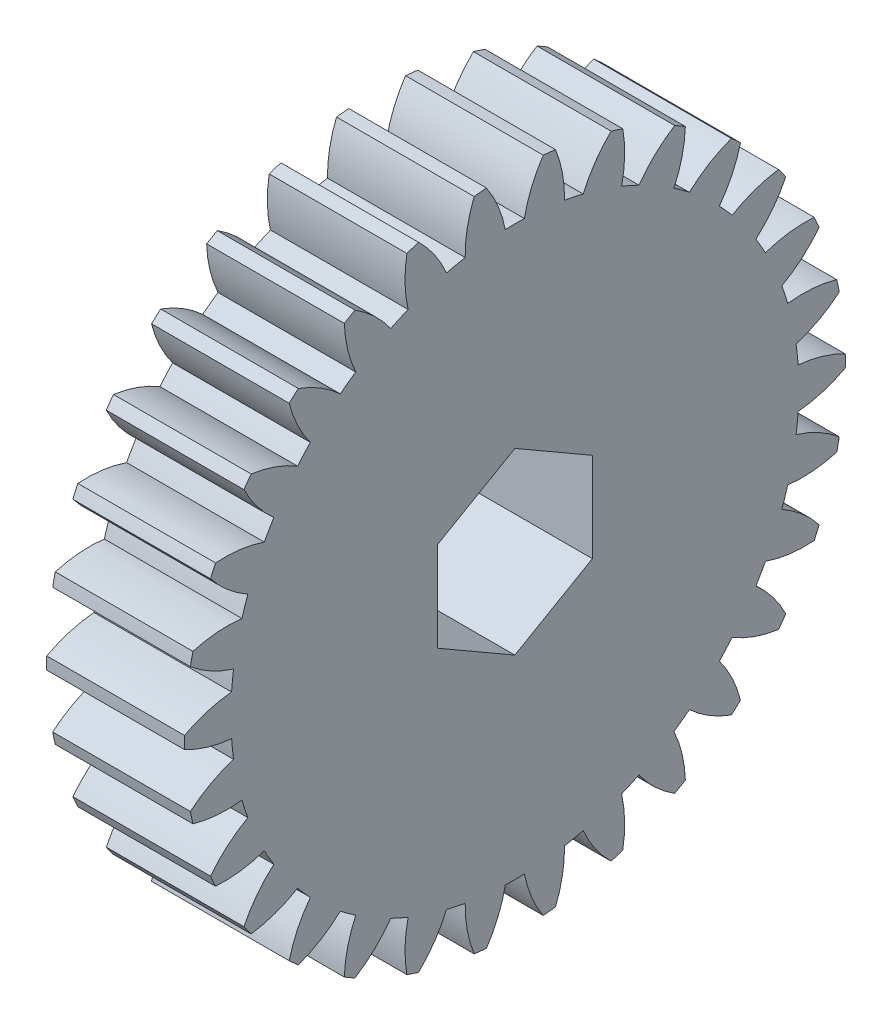
SolidWorks part; units mm, degrees
material "AISI 4340 Aço, normalizado"
ref_plane "Plane1" through (0, 0, 0) normal (0, 0, 1) x (1, 0, 0)
ref_plane "Plane2" through (0, 0, 0) normal (0, 1, 0) x (1, 0, 0)
ref_plane "Plane3" through (0, 0, 0) normal (1, 0, 0) x (0, 0, -1)
sketch "HoldingSke" plane through (0, 0, 0) normal (0, 1, 0) x (1, 0, 0)
  line L0 (0, 0) -> (0.5774, -0.3333)
  line L1 (-15, 0) -> (100, 0) construction
  line L2 (0, 0) -> (-2.1039, 2.3779)
  line L3 (0, 0) -> (-11.863, 4.5341)
  line L4 (0, 0) -> (7.479, 4.318)
  line L5 (0, 0) -> (-46.8476, -17.4728)
  line L6 (0, 0) -> (-12.4344, -8.3896)
  line L7 (-2.1039, 2.3779) -> (8.6586, 51.2059)
  line L8 (-76.2, 54.61) -> (-74.4, 54.61)
  line L9 (-71.009, 38.7566) -> (-53.1078, 45.2721)
  line L10 (-76.2, 71.12) -> (104.1128, 71.12)
  line L11 (0, 0) -> (-15, 0)
  line L12 (-76.2, 101.6) -> (-76.147, 101.6)
  line L13 (24.9733, 27.94) -> (52.9518, 28.4284)
  line L14 (24.9733, 27.94) -> (24.9743, 27.94)
  line L15 (24.9733, 27.94) -> (100.4006, 29.5858)
  line L16 (-63.627, -1.5) -> (-12.827, -1.5)
  circle A0 centre (0, 0) radius 5
  circle A1 centre (0, 0) radius 20.624
  circle A2 centre (0, 0) radius 37.5
  circle A3 centre (0, 0) radius 5
  dimension "MHD" = 41.248
  dimension "Hub_dia" = 75
  dimension "Bore" = 10
  dimension "MBD" = 10
  dimension "Num_teeth" = 30
  dimension "Pitch" = 0.6667
  dimension "Overall_len" = 50
  dimension "Show_teeth" = 30
  dimension "Thickness" = 15
  dimension "OAL" = 50.0001
  dimension "T_dim" = 1.8
  dimension "Ap" = 20
  dimension "H" = 19.05
  dimension "Pitch_radius" = 180.3128
  dimension "Width" = 15
  dimension "Backlash" = 0.053
  dimension "Addendum_fac" = 1
  dimension "Dedendum_fac" = 1.25
  dimension "Clearance_fac" = 0.25
  dimension "Dedendum_add" = 0.001
  dimension "Module" = 1.5
sketch "BasProSke" plane through (0, 0, 0) normal (0, 1, 0) x (1, 0, 0)
  line L0 (-10, 0) -> (60, 0) construction
  line L1 (0, 0) -> (0, 24)
  line L2 (0, 0) -> (15, 0)
  line L3 (15, 0) -> (15, 24)
  line L4 (15, 24) -> (0, 24)
  dimension "Thickness" = 15
  dimension "Diameter" = 48
revolve "Base-Revolve" add sketch "BasProSke" angle 360 about L0
sketch "TooCutSke" plane through (0, 0, 0) normal (1, 0, 0) x (0, 0, -1)
  line L1 (0, 0) -> (0, 107) construction
  line L2 (0, 0) -> (-1.2703, 22.4641) construction
  line L3 (0, 0) -> (-4.6983, 44.7014) construction
  line L4 (-1.2703, 22.4641) -> (-2.3492, 22.3507) construction
  arc A0 (0.6933, 20.6123) -> (-0.6933, 20.6123) centre (0, 0) ccw
  arc A1 (2.0805, 23.9351) -> (-2.0805, 23.9351) centre (0, 0) ccw
  circle A2 centre (0, 0) radius 22.5 construction
  circle A3 centre (0, 0) radius 21.1431 construction
  arc A4 (-0.6933, 20.6123) -> (-2.0805, 23.9351) centre (-9.5243, 18.8764) ccw
  arc A5 (2.0805, 23.9351) -> (0.6933, 20.6123) centre (9.5243, 18.8764) ccw
  dimension "Root_dia" = 41.248
  dimension "Overcut_dia" = 48.0508
  dimension "Pitch_dia" = 45
  dimension "Base_dia" = 42.2862
  dimension "Flank_rad" = 9
  dimension "Half_ang" = 6
  dimension "Half_CT" = 1.0848
extrude "ToothCut" cut sketch "TooCutSke" along normal through all
fillet "Breaks" [suppressed] radius 0.03
fillet "RootFillets" [suppressed] radius 0.376
pattern_circular "TeethCuts" count 30 every 12 about axis through (-10, 0, 0) along (1, 0, 0) of "ToothCut", "RootFillets", "Breaks"
sketch "HubNeaOneSke" plane through (0, 0, 0) normal (-1, 0, 0) x (0, 0, 1)
  circle A0 centre (0, 0) radius 20.624
  dimension "Diameter" = 41.248
extrude "HubNearOne" [suppressed] add sketch "HubNeaOneSke" along normal blind 35.0001
sketch "HubNeaBotSke" plane through (0, 0, 0) normal (-1, 0, 0) x (0, 0, 1)
  circle A0 centre (0, 0) radius 20.624
  dimension "Diameter" = 41.248
extrude "HubNearBoth" [suppressed] add sketch "HubNeaBotSke" along normal blind 17.5
ref_plane "FarPln" through (15, 0, 0) normal (1, 0, 0) x (0, 0, -1)
sketch "HubFarSke" plane through (15, 0, 0) normal (1, 0, 0) x (0, 0, -1)
  circle A0 centre (0, 0) radius 20.624
  dimension "Diameter" = 41.248
extrude "HubFar" [suppressed] add sketch "HubFarSke" along normal blind 17.5
sketch "BorSke" plane through (0, 0, 0) normal (1, 0, 0) x (0, 0, -1)
  circle A0 centre (0, 0) radius 5
  dimension "Diameter" = 10
extrude "Bore" cut sketch "BorSke" along normal mid plane 100.0001
sketch "KeySke" plane through (0, 0, 0) normal (1, 0, 0) x (0, 0, -1)
  line L0 (-2, 0) -> (-2, 6.8)
  line L1 (-2, 6.8) -> (2, 6.8)
  line L2 (2, 6.8) -> (2, 0)
  line L3 (0, 0) -> (0, 34) construction
  line L4 (-2, 0) -> (2, 0)
  dimension "Offset" = 6.8
  dimension "Width" = 4
extrude "Keyway" [suppressed] cut sketch "KeySke" along normal mid plane 100.0001
pattern_circular "Keyway2" [suppressed] count 2 every 90 about axis through (-10, 0, 0) along (1, 0, 0)
sketch "Esboço1" plane through (15, 0, 0) normal (1, 0, 0) x (0, 0, -1)
  line L0 (0, 0) -> (5, 0) construction
  line L1 (0, 6.5) -> (-5.6292, 3.25)
  line L2 (-5.6292, 3.25) -> (-5.6292, -3.25)
  line L3 (-5.6292, -3.25) -> (0, -6.5)
  line L4 (0, -6.5) -> (5.6292, -3.25)
  line L5 (5.6292, -3.25) -> (5.6292, 3.25)
  line L6 (5.6292, 3.25) -> (0, 6.5)
  line L7 (0, 0) -> (0, 6.5) construction
  circle A0 centre (0, 0) radius 5.6292 construction
  circle A1 centre (0, 0) radius 5 construction
  dimension "D1" = 90
  dimension "D2" = 13
extrude "Corte-extrusão1" cut sketch "Esboço1" against normal through all
sketch "Esboço2" plane through (0, 0, 0) normal (-1, 0, 0) x (0, 0, 1)
  circle A0 centre (0, 0) radius 30.6034
extrude "Corte-extrusão2" cut sketch "Esboço2" against normal blind 5
sketch "Esboço4" plane through (5, 0, 0) normal (-1, 0, 0) x (0, 0, 1)
  circle A0 centre (0, 0) radius 9.5
  circle A1 centre (0, 0) radius 7.5
  dimension "D1" = 19
  dimension "D2" = 15
extrude "Ressalto-extrusão1" add sketch "Esboço4" along normal blind 1
equation "' \"Module@HoldingSke\" = 6.35"
equation "' \"Num_teeth@HoldingSke\" = 12"
equation "' \"Ap@HoldingSke\" =  20"
equation "' \"Ap@HoldingSke\" = 20"
equation "' \"Width@HoldingSke\" = 0.5 * 25.4"
equation "' \"Hub_dia@HoldingSke\"= 1 * 25.4"
equation "' \"Hub_dia@HoldingSke\" = 1 * 25.4"
equation "' \"Overall_len@HoldingSke\" = 1.0 * 25.4"
equation "' \"Bore@HoldingSke\" = 0.75 * 25.4"
equation "' \"T_dim@HoldingSke\" = 0.1 * 25.4"
equation "' \"Width@KeySke\" = 0.25 * 25.4"
equation "' \"Show_teeth@HoldingSke\" = 13"
equation "' \"Backlash@HoldingSke\" = 0.009 * 25.4"
equation "' \"Addendum_fac@HoldingSke\" = 1.0"
equation "' \"Dedendum_fac@HoldingSke\" = 1.25"
equation "' \"Dedendum_add@HoldingSke\" = 0.00005 * 25.4"
equation "' \"Clearance_fac@HoldingSke\" = 0.25"
equation "\"Pitch@HoldingSke\" = 1 / \"Module@HoldingSke\""
equation "\"Overcut_dia@TooCutSke\" = (\"Num_teeth@HoldingSke\" + 2 * \"Addendum_fac@HoldingSke\") / \"Pitch@HoldingSke\" + 0.002 * 25.4"
equation "\"Pitch_dia@TooCutSke\" = \"Num_teeth@HoldingSke\" / \"Pitch@HoldingSke\""
equation "\"Base_dia@TooCutSke\" = \"Num_teeth@HoldingSke\" / \"Pitch@HoldingSke\" * cos((\"Ap@HoldingSke\"  * 3.14159265 / 180))"
equation "\"Root_dia@TooCutSke\" = (\"Num_teeth@HoldingSke\" + 2) / \"Pitch@HoldingSke\" - 2 * (\"Addendum_fac@HoldingSke\" + \"Dedendum_fac@HoldingSke\") / \"Pitch@HoldingSke\" - \"Dedendum_add@HoldingSke\" * 2"
equation "\"Half_ang@TooCutSke\" = 180 / \"Num_teeth@HoldingSke\""
equation "\"Half_CT@TooCutSke\" = \"Num_teeth@HoldingSke\" / \"Pitch@HoldingSke\" * sin((3.14159265 / 2 / \"Num_teeth@HoldingSke\")) / 2 - 7 * \"Backlash@HoldingSke\" / 4"
equation "\"Flank_rad@TooCutSke\" = \"Num_teeth@HoldingSke\" / \"Pitch@HoldingSke\" / 5"
equation "\"Radius@RootFillets\" = \"Clearance_fac@HoldingSke\" / \"Pitch@HoldingSke\" + \"Dedendum_add@HoldingSke\""
equation "\"Break_rad@Breaks\" = 0.02 / \"Pitch@HoldingSke\""
equation "\"Thickness@HoldingSke\" = \"Width@HoldingSke\""
equation "\"OAL@HoldingSke\" = \"Thickness@HoldingSke\""
equation "\"MHD@HoldingSke\" = (\"Num_teeth@HoldingSke\" + 2) / \"Pitch@HoldingSke\" - 2 * (\"Addendum_fac@HoldingSke\" + \"Dedendum_fac@HoldingSke\")  / \"Pitch@HoldingSke\" - \"Dedendum_add@HoldingSke\" * 2"
equation "\"MBD@HoldingSke\" = (\"Num_teeth@HoldingSke\" + 2) / \"Pitch@HoldingSke\" - 2 * (\"Addendum_fac@HoldingSke\" + \"Dedendum_fac@HoldingSke\")  / \"Pitch@HoldingSke\" - \"Dedendum_add@HoldingSke\" * 2 - 0.002 * 25.4"
equation "\"MHD@HoldingSke\" = ((sgn( \"MHD@HoldingSke\" - \"Hub_dia@HoldingSke\" )-1)*( \"MHD@HoldingSke\" - \"Hub_dia@HoldingSke\" ))/-2+ \"Hub_dia@HoldingSke\""
equation "\"MBD@HoldingSke\" = ((sgn( \"MBD@HoldingSke\" - \"Bore@HoldingSke\" )-1)*( \"MBD@HoldingSke\" - \"Bore@HoldingSke\" ))/-2+ \"Bore@HoldingSke\""
equation "\"OAL@HoldingSke\" = ((sgn( \"OAL@HoldingSke\" - \"Overall_len@HoldingSke\" )+1)*( \"OAL@HoldingSke\" - \"Overall_len@HoldingSke\" ))/2 + \"Overall_len@HoldingSke\" + 0.000002 * 25.4"
equation "\"Num_teeth@TeethCuts\" = int( \"Show_teeth@HoldingSke\" ) + 1"
equation "\"Num_teeth@TeethCuts\" = ((sgn( \"Num_teeth@TeethCuts\" - \"Num_teeth@HoldingSke\" )-1)*( \"Num_teeth@TeethCuts\" - \"Num_teeth@HoldingSke\" ))/-2+ \"Num_teeth@HoldingSke\""
equation "\"Num_teeth@TeethCuts\" = ((sgn( \"Num_teeth@TeethCuts\" - 2.0)+1)*( \"Num_teeth@TeethCuts\" - 2.0))/2 +2.0"
equation "\"Angle@TeethCuts\" = 360.0 / \"Num_teeth@HoldingSke\""
equation "\"Diameter@BasProSke\" = (\"Num_teeth@HoldingSke\" + 2 * \"Addendum_fac@HoldingSke\") / \"Pitch@HoldingSke\""
equation "\"Thickness@BasProSke\"  = \"Thickness@HoldingSke\""
equation "' \"Fillet_rad@BasProSke\" =  \"Thickness@HoldingSke\" * 0.05"
equation "' \"Fillet_rad@BasProSke\" = \"Thickness@HoldingSke\" * 0.05"
equation "\"MHD@HoldingSke\" = ((sgn( \"MHD@HoldingSke\" - \"Root_dia@TooCutSke\" )-1)*( \"MHD@HoldingSke\" - \"Root_dia@TooCutSke\" ))/-2+ \"Root_dia@TooCutSke\""
equation "\"Diameter@HubNeaOneSke\" = \"MHD@HoldingSke\""
equation "\"Length@HubNearOne\" = \"OAL@HoldingSke\" - \"Thickness@BasProSke\""
equation "\"Diameter@HubNeaBotSke\" = \"MHD@HoldingSke\""
equation "\"Length@HubNearBoth\" = ( \"OAL@HoldingSke\" - \"Thickness@BasProSke\" ) / 2.0"
equation "\"Thickness@FarPln\" = \"Thickness@BasProSke\""
equation "\"Diameter@HubFarSke\" = \"MHD@HoldingSke\""
equation "\"Length@HubFar\" = ( \"OAL@HoldingSke\" - \"Thickness@BasProSke\" ) / 2.0"
equation "\"Diameter@BorSke\" = \"MBD@HoldingSke\""
equation "\"D1@Bore\" = \"OAL@HoldingSke\" * 2.0"
equation "\"D1@Keyway\" = \"OAL@HoldingSke\" * 2.0"
equation "\"Offset@KeySke\" = \"T_dim@HoldingSke\" + \"MBD@HoldingSke\" / 2.0"
